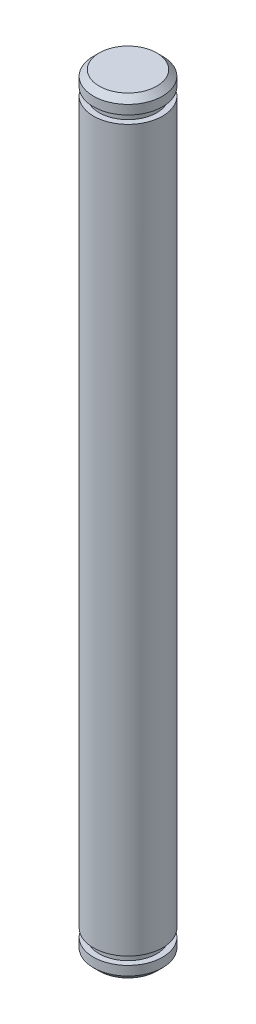
SolidWorks part; units mm, degrees
ref_plane "Front Plane" through (0, 0, 0) normal (0, 0, 1) x (1, 0, 0)
ref_plane "Top Plane" through (0, 0, 0) normal (0, 1, 0) x (1, 0, 0)
ref_plane "Right Plane" through (0, 0, 0) normal (1, 0, 0) x (0, 0, -1)
sketch "Sketch1" plane through (0, 0, 0) normal (0, 1, 0) x (1, 0, 0)
  circle A0 centre (0, 0) radius 3
  dimension "D1" = 6
extrude "50" add sketch "Sketch1" along normal blind 66.5
sketch "Sketch2" plane through (0, 66.5, 0) normal (0, 1, 0) x (1, 0, 0)
  circle A0 centre (0, 0) radius 2.5
  circle A1 centre (0, 0) radius 3 construction
  circle A2 centre (0, 0) radius 3
  dimension "D1" = 5
extrude "Cut-Extrude1" cut sketch "Sketch2" along normal blind 0.7 from offset 2 offset against normal yes
sketch "Sketch3" plane through (0, 0, 0) normal (0, -1, 0) x (1, 0, 0)
  circle A0 centre (0, 0) radius 3 construction
  circle A1 centre (0, 0) radius 2.5 construction
  circle A2 centre (0, 0) radius 3
  circle A3 centre (0, 0) radius 2.5
extrude "Cut-Extrude2" cut sketch "Sketch3" along normal blind 0.7 from offset 2 offset against normal yes
chamfer "Chamfer1" distance 0.5 angle 45 2 edges at (0, 66.5, 3) (0, 0, 3)
